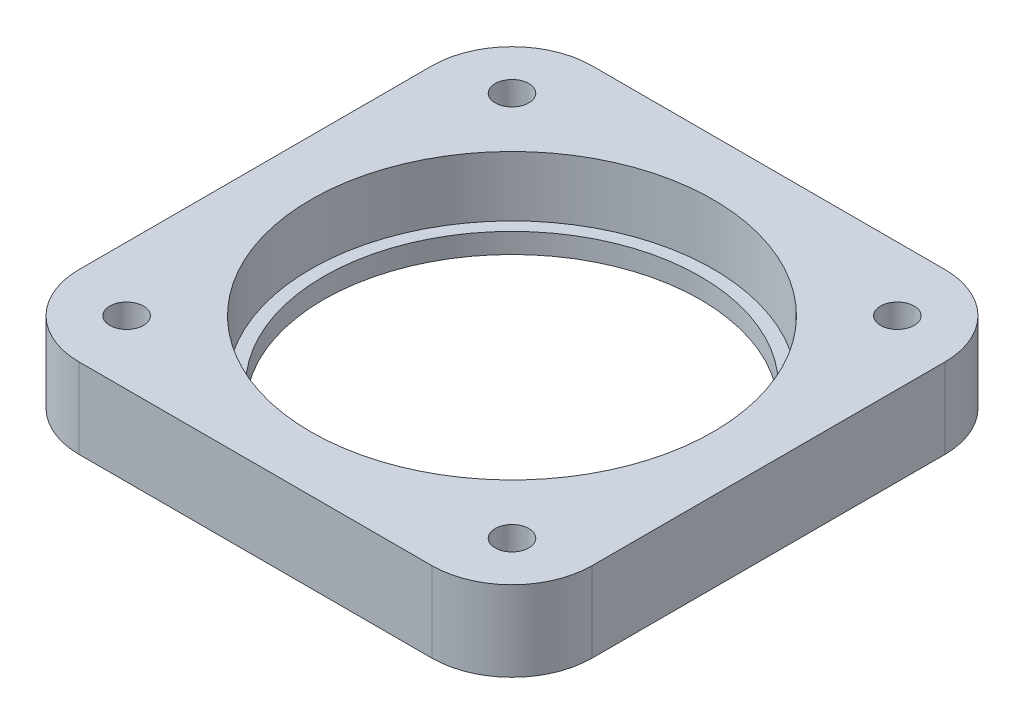
SolidWorks part; units mm, degrees
ref_plane "前视基准面" through (0, 0, 0) normal (0, 0, 1) x (1, 0, 0)
ref_plane "上视基准面" through (0, 0, 0) normal (0, 1, 0) x (1, 0, 0)
ref_plane "右视基准面" through (0, 0, 0) normal (1, 0, 0) x (0, 0, -1)
other "Configuration Table"
sketch "草图1" plane through (0, 0, 0) normal (0, 1, 0) x (1, 0, 0)
  line L1 (-32, -32) -> (32, -32)
  line L2 (-32, -32) -> (-32, 32)
  line L3 (-32, 32) -> (32, 32)
  line L4 (32, -32) -> (32, 32)
  line L5 (-32, -32) -> (32, 32) construction
  line L6 (-32, 32) -> (32, -32) construction
  circle A0 centre (0, 0) radius 23.5
  dimension "D1" = 47
  dimension "D2" = 64
extrude "凸台-拉伸1" add sketch "草图1" along normal blind 2.5
sketch "草图2" plane through (0, 2.5, 0) normal (0, 1, 0) x (1, 0, 0)
  line L1 (-32, -32) -> (32, -32)
  line L2 (-32, -32) -> (-32, 32)
  line L3 (-32, 32) -> (32, 32)
  line L4 (32, -32) -> (32, 32)
  line L5 (-32, -32) -> (32, 32) construction
  line L6 (-32, 32) -> (32, -32) construction
  circle A0 centre (0, 0) radius 25.1
  dimension "D1" = 50.2
extrude "凸台-拉伸2" add sketch "草图2" along normal blind 7.5
sketch "草图3" plane through (0, 10, 0) normal (0, 1, 0) x (1, 0, 0)
  line L0 (0, 0) -> (32, 32) construction
  circle A0 centre (0, 0) radius 34 construction
  circle A1 centre (24.0416, 24.0416) radius 2.1
  circle A2 centre (24.0416, -24.0416) radius 2.1
  circle A3 centre (-24.0416, -24.0416) radius 2.1
  circle A4 centre (-24.0416, 24.0416) radius 2.1
  dimension "D1" = 68
  dimension "D2" = 4.2
  dimension "D3" = 4
extrude "切除-拉伸1" cut sketch "草图3" against normal blind 20
fillet "圆角1" radius 10 4 edges at (32, 5, 32) (-32, 5, 32) (32, 5, -32) (-32, 5, -32)
